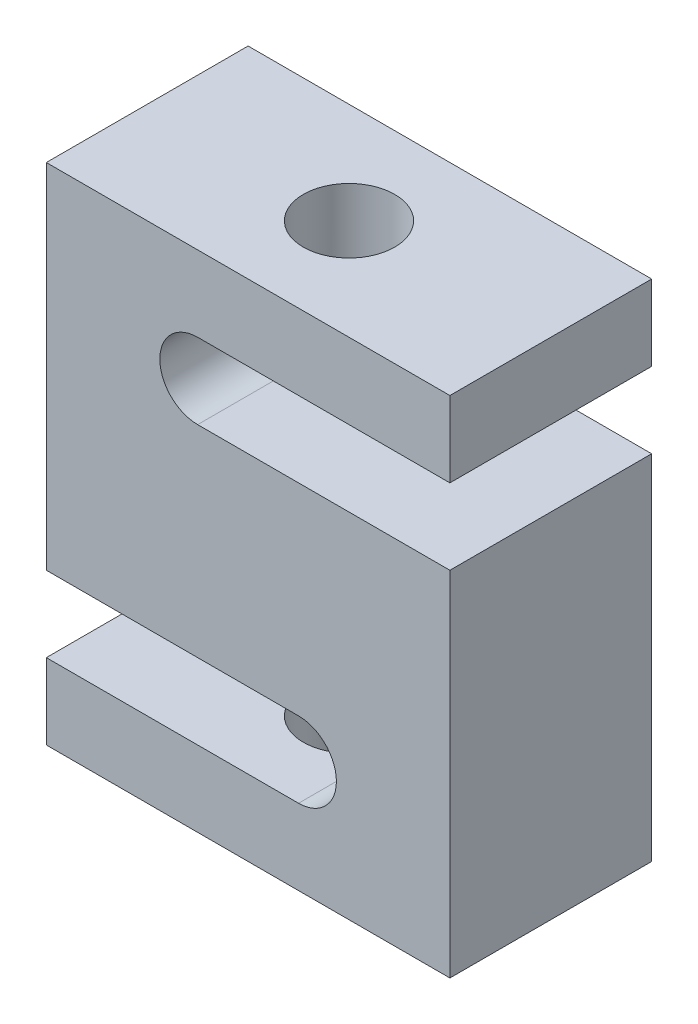
SolidWorks part; units mm, degrees
material "AISI 316 Annealed Stainless Steel Bar (SS)"
ref_plane "Front Plane" through (0, 0, 0) normal (0, 0, 1) x (1, 0, 0)
ref_plane "Top Plane" through (0, 0, 0) normal (0, 1, 0) x (1, 0, 0)
ref_plane "Right Plane" through (0, 0, 0) normal (1, 0, 0) x (0, 0, -1)
sketch "Sketch2" plane through (0, 0, 0) normal (0, 0, 1) x (1, 0, 0)
  line L0 (0, -31.75) -> (50.8, -31.75)
  line L1 (50.8, -31.75) -> (50.8, 12.7)
  line L2 (50.8, 31.75) -> (0, 31.75)
  line L3 (0, 31.75) -> (0, -12.7)
  line L4 (0, -22.225) -> (31.75, -22.225)
  line L5 (31.75, -12.7) -> (0, -12.7)
  line L6 (50.8, 22.225) -> (19.05, 22.225)
  line L7 (19.05, 12.7) -> (50.8, 12.7)
  line L8 (50.8, 22.225) -> (50.8, 31.75)
  line L9 (0, -22.225) -> (0, -31.75)
  arc A0 (31.75, -22.225) -> (31.75, -12.7) centre (31.75, -17.4625) ccw
  arc A1 (19.05, 22.225) -> (19.05, 12.7) centre (19.05, 17.4625) ccw
  dimension "D1" = 50.8
  dimension "D2" = 63.5
  dimension "D3" = 9.525
  dimension "D4" = 9.525
  dimension "D5" = 9.525
  dimension "D6" = 31.75
  dimension "D7" = 31.75
extrude "Boss-Extrude1" add sketch "Sketch2" along normal mid plane 25.4
sketch "Sketch6" plane through (0, 31.75, 0) normal (0, 1, 0) x (1, 0, 0)
  line L0 (50.8, 12.7) -> (0, 12.7) construction
  point P0 (25.4, 0)
  point P3 (26.1148, 0)
  point P8 (25.4, 12.7)
hole_wizard "1/2-20 Tapped Hole1" positions "Sketch6" profile "Sketch5" tap size "1/2-20" standard "ANSI Inch"
sketch "Sketch5" plane through (25.4, 31.75, 0) normal (1, 0, 0) x (0, 0, 1)
  line L0 (0, 0) -> (0, 9.525)
  line L1 (0, 9.525) -> (5.7544, 9.525)
  line L2 (5.7544, 9.525) -> (5.7544, 0)
  line L5 (5.7544, 0) -> (0, 0)
  line L11 (0, -6.35) -> (0, 107.95) construction
  dimension "Thru Tap Drill Dia." = 11.5087
  dimension "Thru Tap Drill Depth" = 9.525
cosmetic thread "Hole Thread1" parameters "D2"=12.7
mirror "Mirror1" about plane through (0, 0, 0) normal (0, 1, 0) of "1/2-20 Tapped Hole1"
cosmetic thread "Hole Thread2" parameters "D2"=12.7
